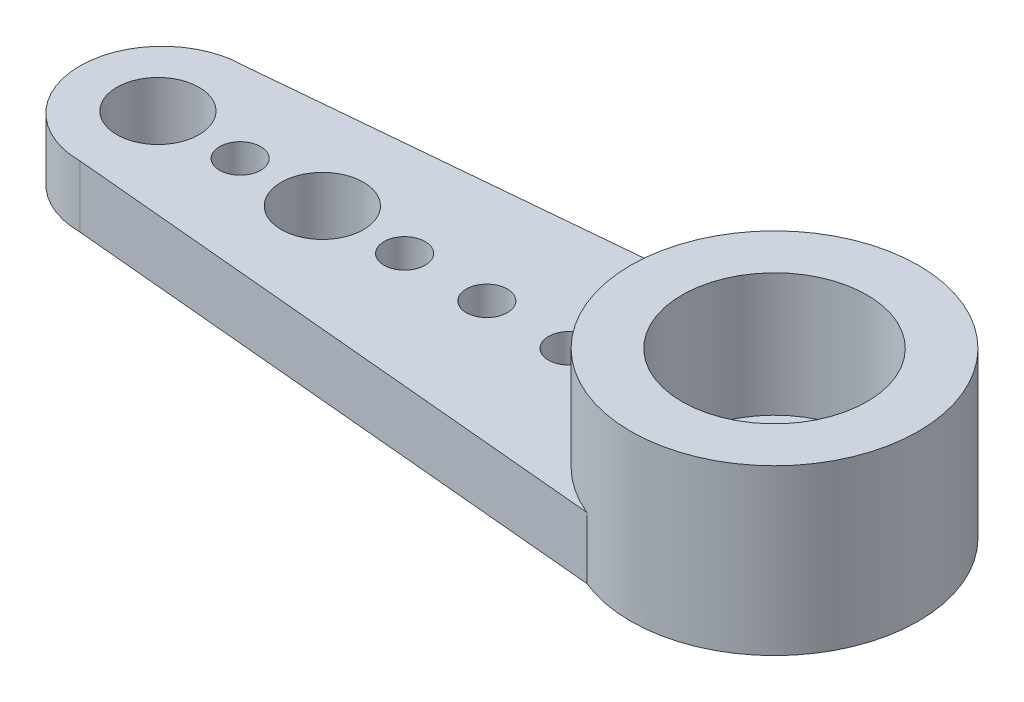
SolidWorks part; units mm, degrees
ref_plane "Front" through (0, 0, 0) normal (0, 0, 1) x (1, 0, 0)
ref_plane "Top" through (0, 0, 0) normal (0, 1, 0) x (1, 0, 0)
ref_plane "Right" through (0, 0, 0) normal (1, 0, 0) x (0, 0, -1)
sketch "Sketch1" plane through (0, 0, 0) normal (0, 1, 0) x (1, 0, 0)
  circle A1 centre (0, 0) radius 3.5
  dimension "D1" = 7
extrude "Boss-Extrude1" add sketch "Sketch1" along normal blind 4
sketch "Sketch6" plane through (0, 0, 0) normal (0, -1, 0) x (1, 0, 0)
  line L0 (0, 0) -> (50000, 0) construction
  line L1 (0, 0) -> (0, -50000) construction
  line L2 (-14.9, 2) -> (-0.65, 3.3014)
  line L3 (-0.65, -3.3014) -> (0, -3.5)
  line L4 (-0.65, 3.3014) -> (0, 3.5)
  line L7 (0, 3.5) -> (0, -3.5)
  line L8 (-0.65, -3.3014) -> (-14.9, -2)
  arc A0 (-14.9, 2) -> (-14.9, -2) centre (-14.9, 0) ccw
  circle A4 centre (0, 0) radius 3.5 construction
  point P7 (-16.9, 0)
  dimension "D1" = 4
  dimension "D2" = 16.9
  dimension "D7" = 6.6028
  dimension "D8" = 10.436
extrude "Boss-Extrude2" add sketch "Sketch6" against normal blind 1.5 contours L2 L4 L7 L3 L8 A0
sketch "Sketch7" plane through (0, 0, 0) normal (0, -1, 0) x (1, 0, 0)
  circle A0 centre (0, 0) radius 2.5
  dimension "D1" = 5
extrude "Cut-Extrude4" cut sketch "Sketch7" against normal blind 0.6
sketch "Sketch8" plane through (0, 4, 0) normal (0, 1, 0) x (1, 0, 0)
  circle A0 centre (0, 0) radius 2.25
  dimension "D1" = 4.5
extrude "Cut-Extrude5" cut sketch "Sketch8" against normal blind 3
sketch "Sketch9" plane through (0, 0.6, 0) normal (0, -1, 0) x (1, 0, 0)
  circle A0 centre (0, 0) radius 1
  dimension "D1" = 2
extrude "Cut-Extrude6" cut sketch "Sketch9" against normal through all
sketch "Sketch10" plane through (0, 0, 0) normal (0, -1, 0) x (1, 0, 0)
  line L0 (0, 0) -> (50000, 0) construction
  line L1 (0, 0) -> (0, -50000) construction
  circle A1 centre (-15, 0) radius 1
  circle A2 centre (-13, 0) radius 0.5
  circle A3 centre (-11, 0) radius 1
  circle A4 centre (-9, 0) radius 0.5
  circle A5 centre (-7, 0) radius 0.5
  circle A6 centre (-5, 0) radius 0.5
  dimension "D1" = 2
  dimension "D6" = 2
  dimension "D7" = 2
  dimension "D8" = 2
  dimension "D3" = 2
  dimension "D4" = 2
  dimension "D5" = 2
  dimension "D2" = 15
extrude "Cut-Extrude7" cut sketch "Sketch10" against normal through all
